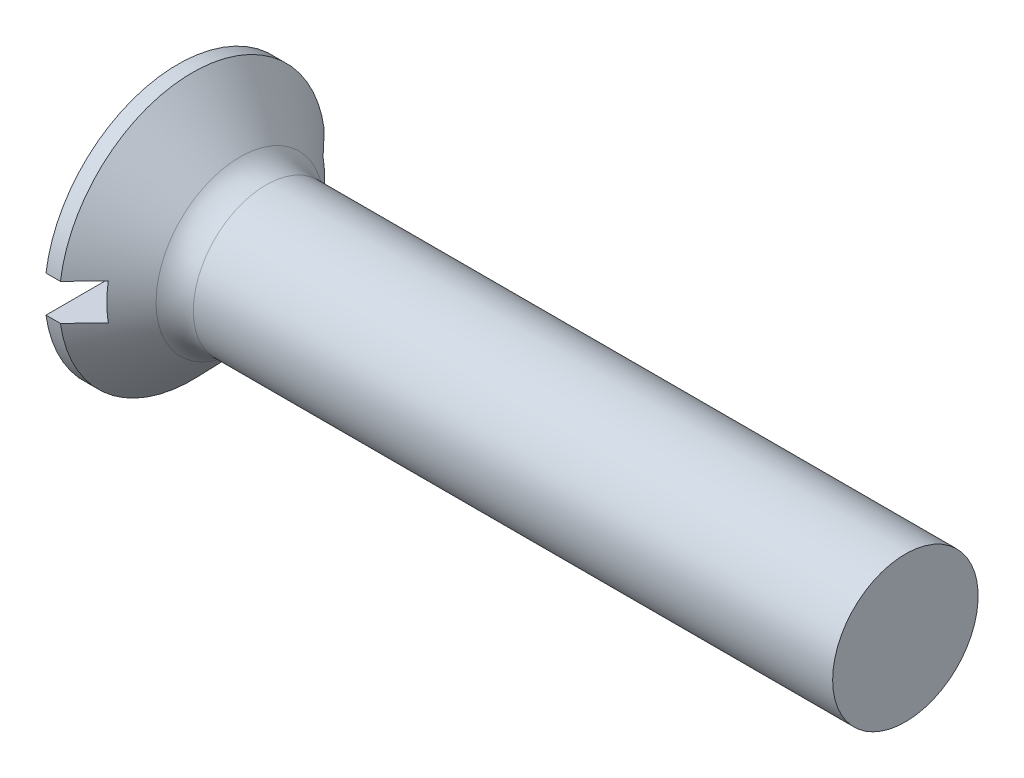
SolidWorks part; units mm, degrees
revolve "Base-Revolve" add sketch "BodySke" angle 360 about L5
sketch "BodySke" plane through (0, 0, 0) normal (0, 0, 1) x (1, 0, 0)
  line L0 (0, 0) -> (0, 9.15)
  line L1 (0, 9.15) -> (0.9924, 9.15)
  line L2 (5, 5) -> (50, 5)
  line L3 (50, 5) -> (50, 0)
  line L4 (50, 0) -> (0, 0)
  line L5 (-6.35, 0) -> (82.55, 0) construction
  line L6 (5, -5) -> (50, -5) construction
  line L7 (0.9924, -9.15) -> (5, -5) construction
  line L8 (0.9924, 9.15) -> (5, 5)
  line L9 (0, -9.15) -> (0.9924, -9.15) construction
  line L10 (6.5, 6.5875) -> (6.5, -2.9375) construction
  line L11 (0, 6.35) -> (0, -3.175) construction
  dimension "Diameter" = 10
  dimension "Length" = 50
  dimension "Head_ht" = 5
  dimension "Head_dia" = 18.3
  dimension "Head_ang" = 92
  dimension "D6" = 0.9924
  dimension "Advance" = 1.5
  dimension "Thread_nom" = 50
cosmetic thread "ThreadCosmetic" [suppressed] parameters "Thread_length"=43.5, "Thread_minor"=7.9248
extrude "Slot" cut sketch "Sketch2" against normal blind 2.6
sketch "Sketch2" plane through (0, 0, 0) normal (-1, 0, 0) x (0, 0, 1)
  line L0 (-9.15, -1.25) -> (9.15, -1.25)
  line L1 (-9.15, -1.25) -> (-9.15, 1.25)
  line L2 (9.15, 1.25) -> (-9.15, 1.25)
  line L3 (9.15, 1.25) -> (9.15, -1.25)
  dimension "Slot_width" = 2.5
  dimension "D1" = 1.25
  dimension "D2" = 18.3
  dimension "D3" = 9.15
ref_plane "Plane1" through (0, 0, 0) normal (0, 0, 1) x (1, 0, 0)
ref_plane "Plane2" through (0, 0, 0) normal (0, 1, 0) x (1, 0, 0)
ref_plane "Plane3" through (0, 0, 0) normal (1, 0, 0) x (0, 0, -1)
fillet "Fillet1" radius 2.5 1 edges at (5, 0, 5)
sketch "ThdSchSke" plane through (0, 0, 0) normal (0, 0, 1) x (1, 0, 0)
  line L0 (6.5, -3.9624) -> (5.7735, -5)
  line L1 (6.5, -3.9624) -> (7.2265, -5)
  line L2 (7.2265, -5) -> (7.2265, -6.25)
  line L3 (-3.175, 0) -> (5.1513, 0) construction
  line L5 (7.2265, -6.25) -> (5.7735, -6.25)
  line L6 (5.7735, -6.25) -> (5.7735, -5)
  line L7 (0, 9.15) -> (0, 1.25) construction
  dimension "Diameter" = 10
  dimension "Thread_minor" = 7.9248
  dimension "Start" = 6.5
revolve "ThreadSchematic" [suppressed] cut sketch "ThdSchSke" angle 360 about L3
pattern_linear "ThdSchPat" [suppressed]
equation "\"D1@Sketch2\" = \"Slot_width@Sketch2\" / 2"
equation "\"D2@Sketch2\" = \"Head_dia@BodySke\""
equation "\"D3@Sketch2\" = \"D2@Sketch2\" / 2"
equation "\"Thread_length@ThreadCosmetic\" = ((sgn( (\"Length@BodySke\" - \"Advance@BodySke\" * 1.0 - \"Head_ht@BodySke\" ) - \"Thread_nom@BodySke\" )-1)*( (\"Length@BodySke\" - \"Advance@BodySke\" * 1.0 - \"Head_ht@BodySke\" ) - \"Thread_nom@BodySke\" ))/-2+ \"Thread_nom@BodySke\""
equation "\"Thread_minor@ThdSchSke\" = \"Thread_minor@ThreadCosmetic\""
equation "\"Diameter@ThdSchSke\" = \"Diameter@BodySke\""
equation "\"Overcut@ThdSchSke\" = \"Diameter@BodySke\" * 1.25"
equation "\"Start@ThdSchSke\" = 0.000001 + \"Length@BodySke\" - \"Thread_length@ThreadCosmetic\"  '---Countersunk---"
equation "\"Num_threads@ThdSchPat\" = int( \"Thread_length@ThreadCosmetic\" / \"Advance@BodySke\" + 0.999 )  + 1"
equation "\"Advance@ThdSchPat\" = \"Thread_length@ThreadCosmetic\" /  (\"Num_threads@ThdSchPat\" - 1) 'relax it"
